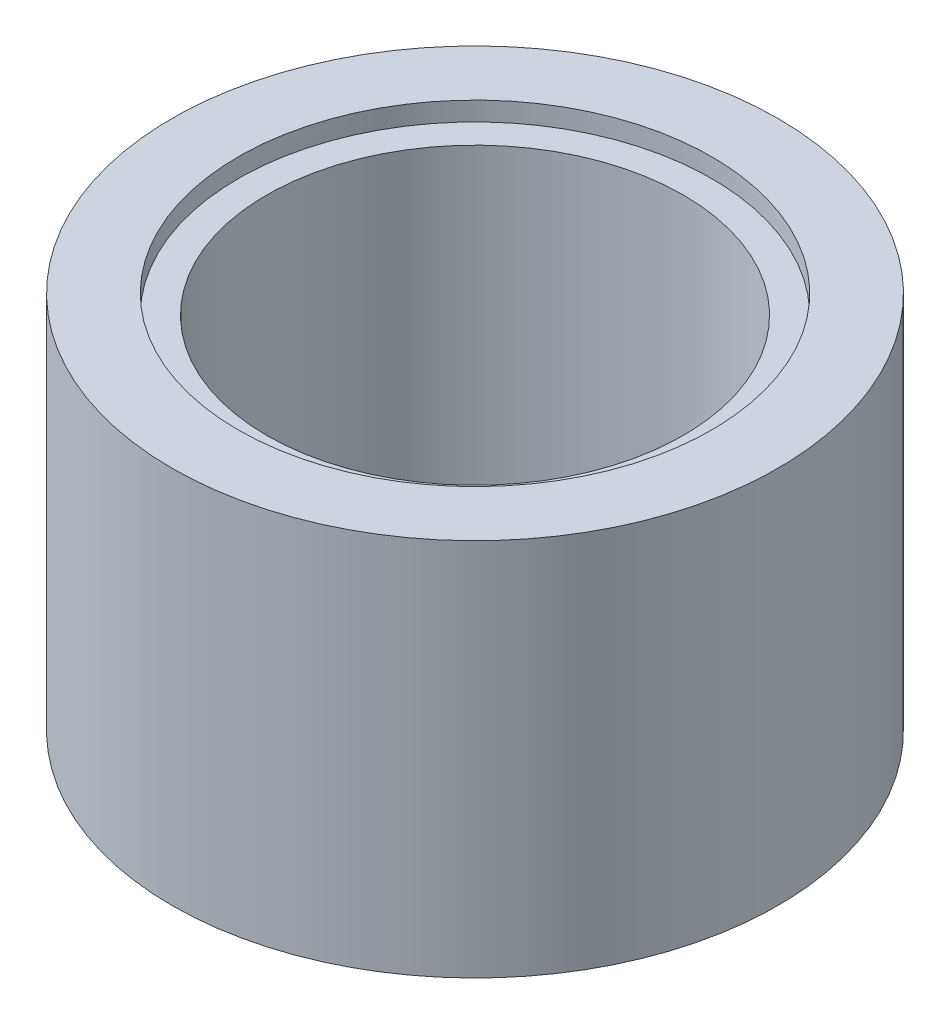
SolidWorks part; units mm, degrees
material "Borracha de silicone"
ref_plane "Plano frontal" through (0, 0, 0) normal (0, 0, 1) x (1, 0, 0)
ref_plane "Plano superior" through (0, 0, 0) normal (0, 1, 0) x (1, 0, 0)
ref_plane "Plano direito" through (0, 0, 0) normal (1, 0, 0) x (0, 0, -1)
sketch "Esboço1" plane through (0, 0, 0) normal (0, 0, 1) x (1, 0, 0)
  line L0 (12.5, 10.814) -> (12.5, 9.814)
  line L1 (12.5, 9.814) -> (11, 9.814)
  line L2 (11, 9.814) -> (11, -8.186)
  line L3 (11, -8.186) -> (12.5, -8.186)
  line L4 (12.5, -8.186) -> (12.5, -9.186)
  line L5 (12.5, -9.186) -> (16, -9.186)
  line L6 (16, -9.186) -> (16, 10.814)
  line L7 (16, 10.814) -> (12.5, 10.814)
  line L8 (0, 52.8694) -> (0, -38.2428) construction
  dimension "D1" = 16
  dimension "D2" = 12.5
  dimension "D3" = 11
  dimension "D4" = 12.5
  dimension "D5" = 20
  dimension "D6" = 1
  dimension "D7" = 18
revolve "Revolução1" add sketch "Esboço1" angle 360 about L8
sketch "Esboço2" plane through (0, 10.814, 0) normal (0, 1, 0) x (1, 0, 0)
  text T0 "<b><i>ROBOCORE</i></b>" font "Century Gothic" height 3
extrude "Ressalto-extrusão1" add sketch "Esboço2" against normal blind 20.2
sketch "Esboço3" plane through (0, -8.186, 0) normal (0, -1, 0) x (1, 0, 0)
  circle A0 centre (0, 0) radius 12.5
extrude "Corte-extrusão1" cut sketch "Esboço3" along normal blind 20.2
sketch "Esboço4" plane through (0, 9.814, 0) normal (0, 1, 0) x (1, 0, 0)
  circle A0 centre (0, 0) radius 12.5
extrude "Corte-extrusão2" cut sketch "Esboço4" along normal blind 20.2
